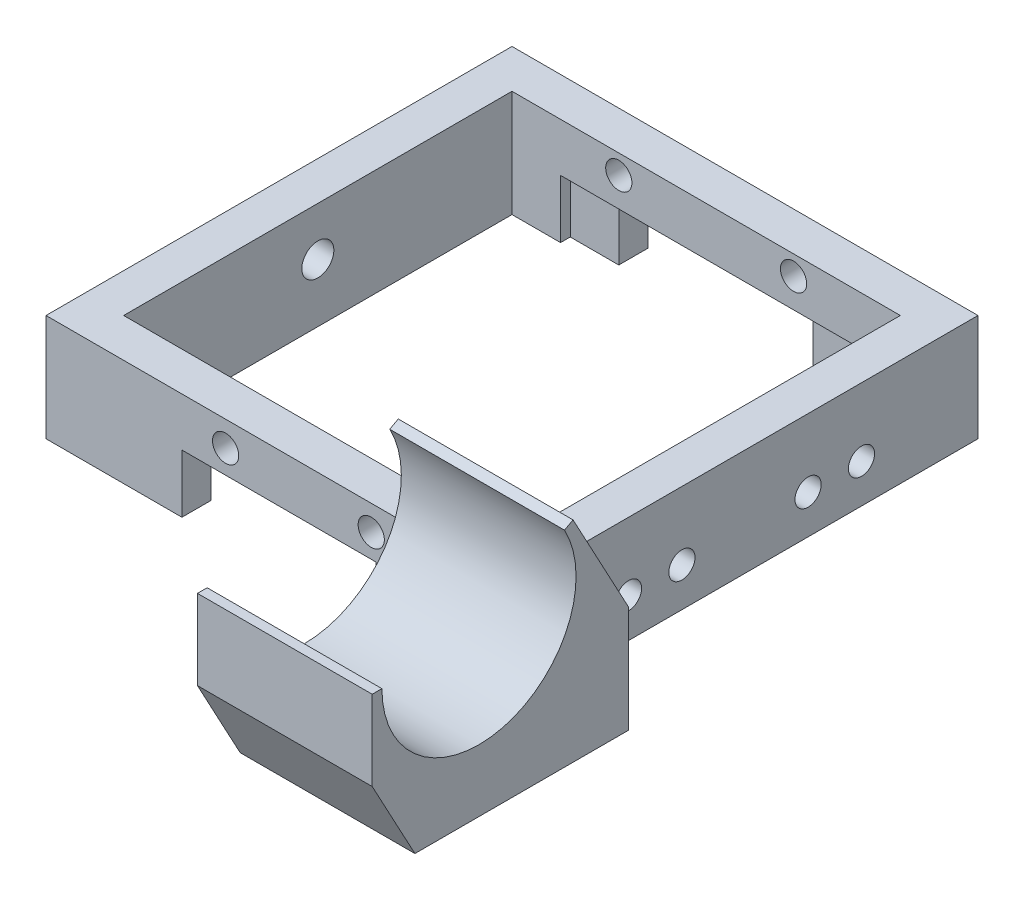
SolidWorks part; units mm, degrees
ref_plane "Front Plane" through (0, 0, 0) normal (0, 0, 1) x (1, 0, 0)
ref_plane "Top Plane" through (0, 0, 0) normal (0, 1, 0) x (1, 0, 0)
ref_plane "Right Plane" through (0, 0, 0) normal (1, 0, 0) x (0, 0, -1)
sketch "Sketch1" plane through (0, 0, 0) normal (0, 1, 0) x (1, 0, 0)
  line L0 (-20, 20) -> (20, -20) construction
  line L1 (-20, 20) -> (20, 20)
  line L2 (-20, 20) -> (-20, -20)
  line L3 (-20, -20) -> (20, -20)
  line L4 (20, 20) -> (20, -20)
  line L5 (-20, -20) -> (20, 20) construction
  line L6 (-24, 24) -> (-24, -24)
  line L7 (-24, -24) -> (24, -24)
  line L8 (24, 24) -> (24, -24)
  line L9 (-24, 24) -> (24, 24)
  point P4 (0, 0)
  dimension "D1" = 40
  dimension "D2" = 40
  dimension "D3" = 4
extrude "Boss-Extrude1" add sketch "Sketch1" along normal blind 11
sketch "Sketch3" plane through (0, 0, 24) normal (0, 0, 1) x (1, 0, 0)
  line L0 (-24, 0) -> (24, 0) construction
  line L1 (-10, 0) -> (10, 0)
  line L2 (-10, 0) -> (-10, 6)
  line L3 (-10, 6) -> (10, 6)
  line L4 (10, 0) -> (10, 6)
  point P6 (0, 6)
  dimension "D1" = 6
  dimension "D2" = 20
extrude "Cut-Extrude1" cut sketch "Sketch3" against normal through all
sketch "Sketch4" plane through (0, 0, -20) normal (0, 0, 1) x (1, 0, 0)
  line L1 (-10, 0) -> (-15, 0)
  line L2 (-10, 0) -> (-10, 6)
  line L3 (-10, 6) -> (-15, 6)
  line L4 (-15, 0) -> (-15, 6)
  line L5 (10, 0) -> (15, 0)
  line L6 (10, 0) -> (10, 6)
  line L7 (10, 6) -> (15, 6)
  line L8 (15, 0) -> (15, 6)
  dimension "D1" = 6
  dimension "D2" = 6
  dimension "D3" = 5
  dimension "D4" = 5
sketch "Sketch5" plane through (0, 0, 20) normal (0, 0, -1) x (-1, 0, 0)
  line L4 (-15, 0) -> (-10, 0)
  line L5 (-15, 6) -> (-15, 0)
  line L6 (-10, 6) -> (-15, 6)
  line L7 (-10, 0) -> (-10, 6)
  line L8 (10, 6) -> (10, 0)
  line L9 (10, 0) -> (20, 0)
  line L10 (20, 0) -> (20, 11)
  line L11 (20, 11) -> (-20, 11)
  line L12 (-20, 11) -> (-20, 0)
  line L13 (-20, 0) -> (-10, 0)
  line L14 (-10, 0) -> (-10, 6)
  line L15 (-10, 6) -> (10, 6)
  line L16 (10, 6) -> (10, 0)
  line L17 (10, 0) -> (20, 0)
  line L18 (20, 0) -> (20, 11)
  line L19 (20, 11) -> (-20, 11)
  line L20 (-20, 11) -> (-20, 0)
  line L21 (-20, 0) -> (-10, 0)
  line L22 (-10, 0) -> (-10, 6)
  line L23 (-10, 6) -> (10, 6)
  line L24 (-15, 0) -> (-10, 0)
  line L25 (-15, 6) -> (-15, 0)
  line L26 (-10, 6) -> (-15, 6)
  line L27 (-10, 0) -> (-10, 6)
  line L28 (10, 0) -> (15, 0)
  line L29 (15, 0) -> (15, 6)
  line L30 (15, 6) -> (10, 6)
  line L31 (10, 6) -> (10, 0)
  line L32 (10, 0) -> (15, 0)
  line L33 (15, 0) -> (15, 6)
  line L34 (15, 6) -> (10, 6)
  line L35 (10, 6) -> (10, 0)
  line M9 (10, 6) -> (10, 0)
  line M10 (10, 0) -> (20, 0)
  line M15 (-10, 0) -> (-10, 6)
  dimension "D1" = 0
  dimension "D2" = 0
  dimension "D3" = 0
extrude "Cut-Extrude2" cut sketch "Sketch4" against normal blind 1
extrude "Cut-Extrude3" cut sketch "Sketch5" against normal blind 1 contours L26 L25 L21 M15 | L33 L34 M9 M10
sketch "Sketch6" plane through (0, 0, -24) normal (0, 0, -1) x (-1, 0, 0)
  line L0 (-9, 9) -> (9, 9) construction
  line L1 (24, 11) -> (24, 0) construction
  line L2 (-24, 11) -> (24, 11) construction
  circle A0 centre (-9, 9) radius 1.35
  circle A1 centre (9, 9) radius 1.35
  point P4 (0, 9)
  dimension "D3" = 2.7
  dimension "D4" = 2.7
  dimension "D1" = 15
  dimension "D2" = 2
extrude "Cut-Extrude4" cut sketch "Sketch6" against normal up to next
sketch "Sketch7" plane through (0, 0, 24) normal (0, 0, 1) x (1, 0, 0)
  line L0 (24, 11) -> (24, 0) construction
  circle A0 centre (9.5, 8.4128) radius 1.35
  circle A1 centre (-5.5, 8.4128) radius 1.35
  dimension "D1" = 2.7
  dimension "D2" = 2.7
  dimension "D3" = 14.5
  dimension "D4" = 15
extrude "Cut-Extrude5" cut sketch "Sketch7" against normal up to next
sketch "Sketch8" plane through (24, 0, 0) normal (1, 0, 0) x (0, 0, -1)
  line L0 (-24, 11) -> (-24, 0) construction
  line L1 (-24, 0) -> (24, 0) construction
  line L2 (0, 0) -> (0, 11) construction
  line L3 (-24, 11) -> (24, 11) construction
  circle A0 centre (-12, 4) radius 1.35
  circle A1 centre (-6.5, 4) radius 1.35
  circle A2 centre (6.5, 4) radius 1.35
  circle A3 centre (12, 4) radius 1.35
  dimension "D3" = 2.7
  dimension "D4" = 2.7
  dimension "D1" = 12
  dimension "D2" = 5.5
  dimension "D5" = 4
extrude "Cut-Extrude6" cut sketch "Sketch8" against normal up to next
sketch "Sketch9" plane through (-24, 0, 0) normal (-1, 0, 0) x (0, 0, 1)
  line L0 (-24, 0) -> (24, 0) construction
  circle A0 centre (0, 6) radius 1.65
  dimension "D2" = 3.3
  dimension "D1" = 6
extrude "Cut-Extrude7" cut sketch "Sketch9" against normal up to next
sketch "Sketch10" plane through (24, 0, 0) normal (1, 0, 0) x (0, 0, -1)
  line L3 (-20, 0) -> (-42, 0)
  line L6 (-24, 0) -> (24, 0) construction
  line L7 (-20, 0) -> (-20, 11)
  line L8 (-20, 11) -> (20, 11) construction
  line L9 (-20, 11) -> (20, 11) construction
  line L10 (-46.4, 8.1827) -> (-42, 0)
  line L12 (-20, 11) -> (-25.7118, 21.6223)
  line L13 (-46.4, 8.1827) -> (-46.4, 16.4128)
  line L14 (-46.4, 16.4128) -> (-45.4, 16.4128)
  line L15 (-26.5926, 21.1487) -> (-25.7118, 21.6223)
  circle A0 centre (-35.4, 16.4128) radius 8.5 construction
  arc A2 (-45.4, 16.4128) -> (-26.5926, 21.1487) centre (-35.4, 16.4128) ccw
  arc A3 (-46.4, 16.4128) -> (-25.7118, 21.6223) centre (-35.4, 16.4128) ccw
  line M6 (-24, 0) -> (24, 0)
  line M8 (24, 11) -> (-24, 11)
  line M9 (-24, 11) -> (-24, 0)
  dimension "D2" = 17
  dimension "D1" = 20
  dimension "D3" = 22
  dimension "D4" = 22
extrude "Boss-Extrude7" add sketch "Sketch10" along normal blind 8 and the other way blind 10 contours A3 L13 L3 L12 M9 M8 | L14 A3 L15 A2 | L7 M6 M8 M9
